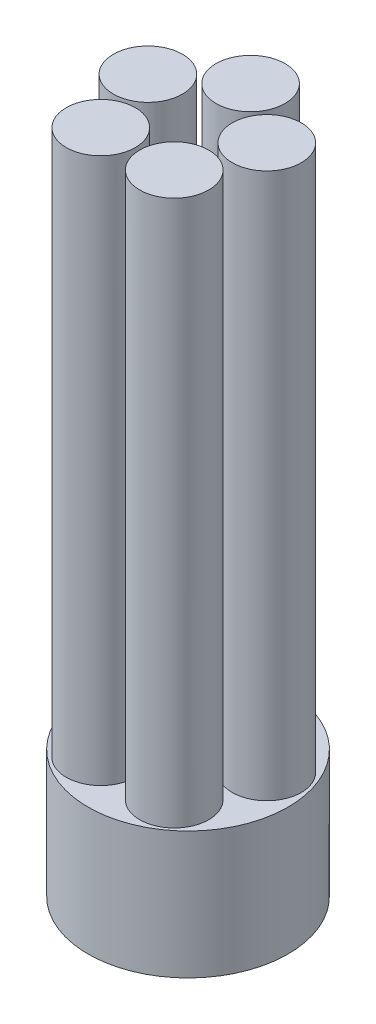
SolidWorks part; units mm, degrees
ref_plane "Front Plane" through (0, 0, 0) normal (0, 0, 1) x (1, 0, 0)
ref_plane "Top Plane" through (0, 0, 0) normal (0, 1, 0) x (1, 0, 0)
ref_plane "Right Plane" through (0, 0, 0) normal (1, 0, 0) x (0, 0, -1)
sketch "Sketch1" plane through (0, 0, 0) normal (0, 1, 0) x (1, 0, 0)
  line L0 (0, 0) -> (0, 68.7343) construction
  line L1 (0, 0) -> (65.3702, 21.2401) construction
  line L2 (0, 0) -> (40.401, -55.6072) construction
  line L3 (0, 0) -> (-40.401, -55.6072) construction
  line L4 (0, 0) -> (-65.3702, 21.2401) construction
  circle A0 centre (0, 0) radius 110
  circle A1 centre (0, 68.7343) radius 38
  circle A2 centre (65.3702, 21.2401) radius 38
  circle A3 centre (40.401, -55.6072) radius 38
  circle A4 centre (-40.401, -55.6072) radius 38
  circle A5 centre (-65.3702, 21.2401) radius 38
  point P13 (0, 68.7343)
  dimension "D1" = 220
  dimension "D2" = 76
  dimension "D3" = 72
  dimension "D4" = 72
  dimension "D5" = 72
  dimension "D6" = 72
extrude "Boss-Extrude1" add sketch "Sketch1" along normal blind 600 contours A2 | A3 | A4 | A5 | A1
sketch "Sketch2" plane through (0, 0, 0) normal (0, -1, 0) x (1, 0, 0)
  circle A0 centre (0, 0) radius 110
  dimension "D1" = 220
extrude "Boss-Extrude2" add sketch "Sketch2" along normal blind 140
